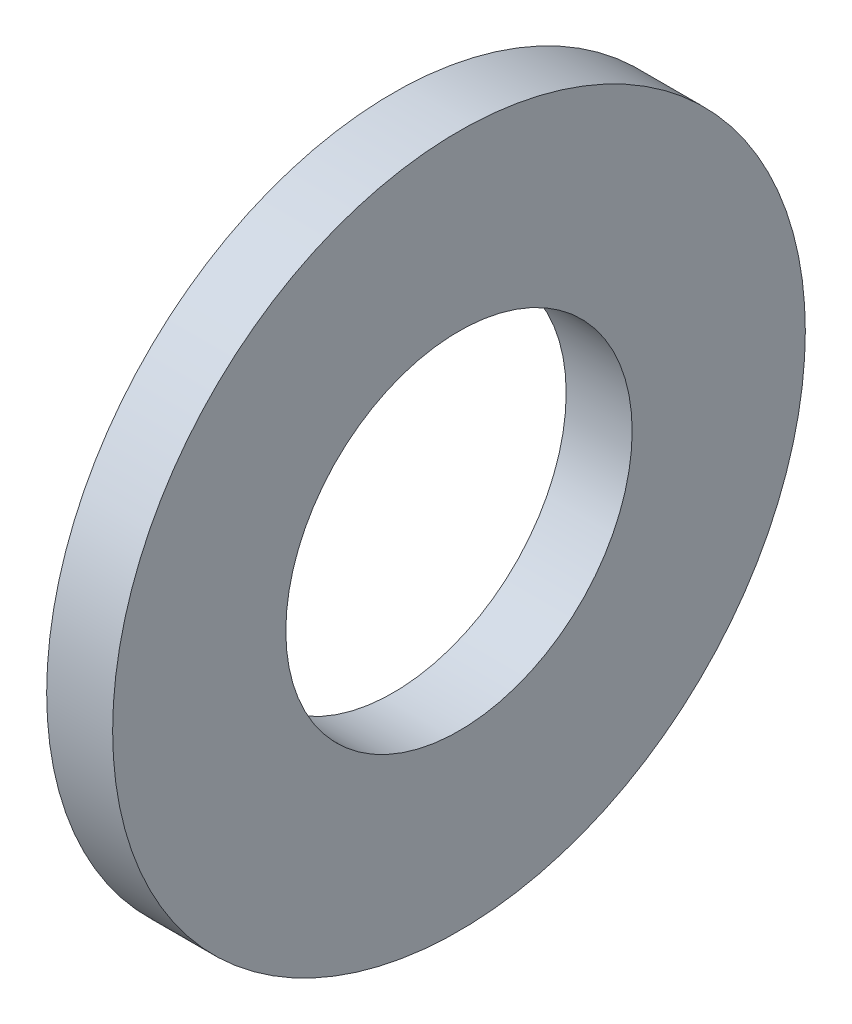
SolidWorks part; units mm, degrees
ref_plane "Front" through (0, 0, 0) normal (0, 0, 1) x (1, 0, 0)
ref_plane "Top" through (0, 0, 0) normal (0, 1, 0) x (1, 0, 0)
ref_plane "Right" through (0, 0, 0) normal (1, 0, 0) x (0, 0, -1)
sketch "Sketch1" plane through (0, 0, 0) normal (0, 0, 1) x (1, 0, 0)
  line L0 (0, 5.25) -> (2, 5.25)
  line L1 (2, 5.25) -> (2, 10.5)
  line L2 (2, 10.5) -> (0, 10.5)
  line L3 (0, 10.5) -> (0, 5.25)
  line L4 (4.0462, 0) -> (-1.0028, 0) construction
  dimension "D1" = 10.5
  dimension "D2" = 21
  dimension "D3" = 2
revolve "Revolve1" add sketch "Sketch1" angle 360 about L4
